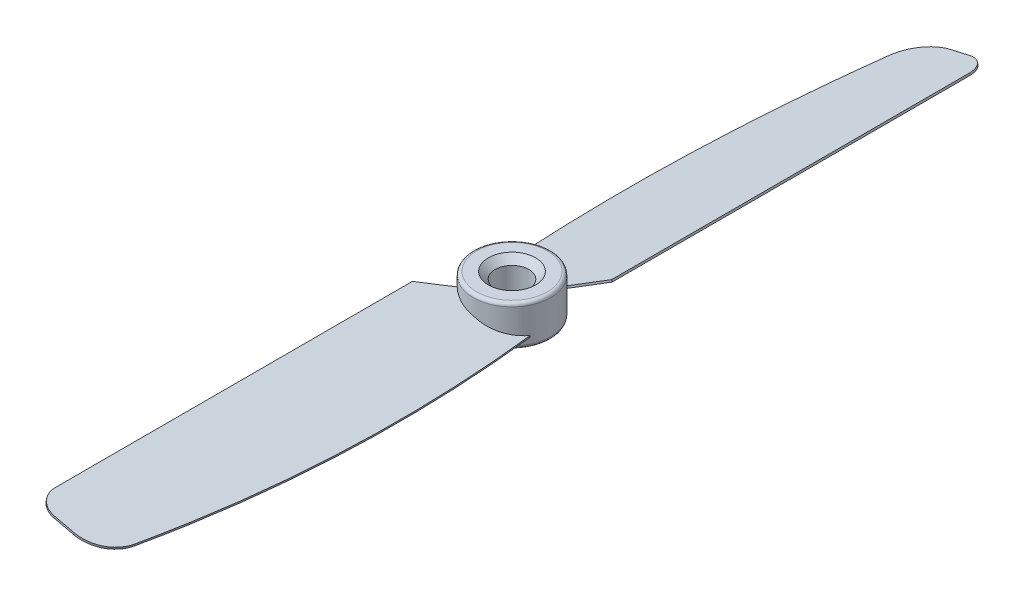
SolidWorks part; units mm, degrees
ref_plane "Front Plane" through (0, 0, 0) normal (0, 0, 1) x (1, 0, 0)
ref_plane "Top Plane" through (0, 0, 0) normal (0, 1, 0) x (1, 0, 0)
ref_plane "Right Plane" through (0, 0, 0) normal (1, 0, 0) x (0, 0, -1)
sketch "Sketch1" plane through (0, 0, 0) normal (0, 1, 0) x (1, 0, 0)
  circle A0 centre (0, 0) radius 5.75
  dimension "D1" = 11.5
extrude "Boss-Extrude1" add sketch "Sketch1" along normal mid plane 6
sketch "Sketch2" plane through (0, 0, 0) normal (0, 0, 1) x (1, 0, 0)
  line L0 (-5.75, 1.3275) -> (5.75, -1.3275) construction
  line L1 (-5.75, 3) -> (-5.75, -3) construction
  line L2 (5.75, -3) -> (5.75, 3) construction
  line L3 (-5.75, -3) -> (5.75, -3) construction
  point P6 (0, 0)
  dimension "D1" = 13
ref_plane "Plane1" through (0, 0, 0) normal (-0.225, -0.9744, 0) x (0.9744, -0.225, 0)
sketch "Sketch3" plane through (0, 0, 0) normal (-0.225, -0.9744, 0) x (0.9744, -0.225, 0)
  line L0 (-3.6524, 3.6524) -> (-7.4983, 7.4983)
  line L1 (-7.4983, 7.4983) -> (-7.4983, 60.5)
  line L2 (-4.4983, 63.5) -> (-1.4647, 63.5)
  arc A0 (3.4623, 59.351) -> (-1.4647, 63.5) centre (-1.4647, 58.5) ccw
  arc A1 (-7.4983, 60.5) -> (-4.4983, 63.5) centre (-4.4983, 60.5) cw
  ellipse E1 centre (0.6749, 0) end of major axis (0.6749, 5.75) minor radius 5.6026 construction
  ellipse E2 centre (0.6749, 0) end of major axis (0.6749, 5.75) minor radius 5.6026 (5.5794, 2.7796) -> (-3.6524, 3.6524) ccw
  spline S0 degree 3 poles (5.5794, 2.7796) (7.4047, 21.7347) (6.6976, 40.6199) (3.4623, 59.351) knots 0 0 0 0 0.93121 0.93121 0.93121 0.93121
  dimension "D2" = 5
  dimension "D3" = 3
extrude "Boss-Extrude2" add sketch "Sketch3" along normal mid plane 0.3
pattern_circular "CirPattern1" count 2 over 360 about axis through (0, 3, 0) along (0, -1, 0) of "Boss-Extrude2"
sketch "Sketch4" plane through (0, -3, 0) normal (0, -1, 0) x (1, 0, 0)
  circle A0 centre (0, 0) radius 2.5
  dimension "D1" = 5
extrude "Cut-Extrude1" cut sketch "Sketch4" against normal through all
fillet "Fillet1" radius 0.5 2 edges at (0, 3, 5.75) (0, -3, 5.75)
chamfer "Chamfer1" distance 1 angle 45 1 edges at (0, -3, -2.5)
chamfer "Chamfer2" distance 1 angle 45 1 edges at (0, 3, -2.5)
